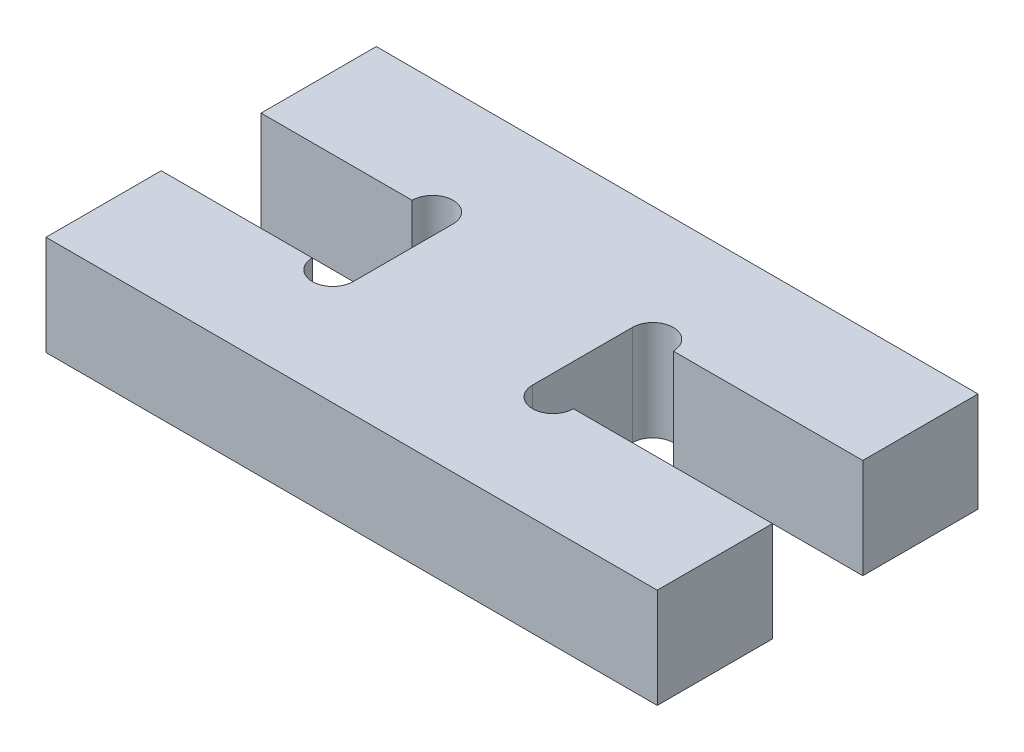
SolidWorks part; units mm, degrees
ref_plane "Front Plane" through (0, 0, 0) normal (0, 0, 1) x (1, 0, 0)
ref_plane "Top Plane" through (0, 0, 0) normal (0, 1, 0) x (1, 0, 0)
ref_plane "Right Plane" through (0, 0, 0) normal (1, 0, 0) x (0, 0, -1)
sketch "Sketch1" plane through (0, 0, 0) normal (0, 1, 0) x (1, 0, 0)
  line L0 (0, 0) -> (0, 9)
  line L1 (0, 9) -> (15, 9)
  line L2 (15, 9) -> (15, 16.8)
  line L3 (15, 16.8) -> (0, 16.8)
  line L4 (0, 16.8) -> (0, 25.8)
  line L5 (0, 25.8) -> (47, 25.8)
  line L6 (47, 25.8) -> (47, 16.8)
  line L7 (47, 16.8) -> (29, 16.8)
  line L8 (29, 16.8) -> (29, 9)
  line L9 (29, 9) -> (47.7474, 9)
  line L10 (47.7474, 9) -> (47.7474, 0)
  line L11 (47.7474, 0) -> (0, 0)
  circle A4 centre (13.4, 16.8) radius 1.6
  circle A5 centre (30.6, 16.8) radius 1.6
  circle A6 centre (30.6, 9) radius 1.6
  circle A7 centre (13.4, 9) radius 1.6
  dimension "D9" = 3.2
  dimension "D10" = 3.2
  dimension "D11" = 3.2
  dimension "D12" = 3.2
  dimension "D1" = 9
  dimension "D2" = 15
  dimension "D3" = 7.8
  dimension "D4" = 9
  dimension "D5" = 9
  dimension "D6" = 9
  dimension "D7" = 18
  dimension "D8" = 14
extrude "Boss-Extrude1" add sketch "Sketch1" along normal blind 7.8 contours A7 L1 L0 L11 L10 L9 A6 L8 A5 L7 L6 L5 L4 L3 A4 L2
